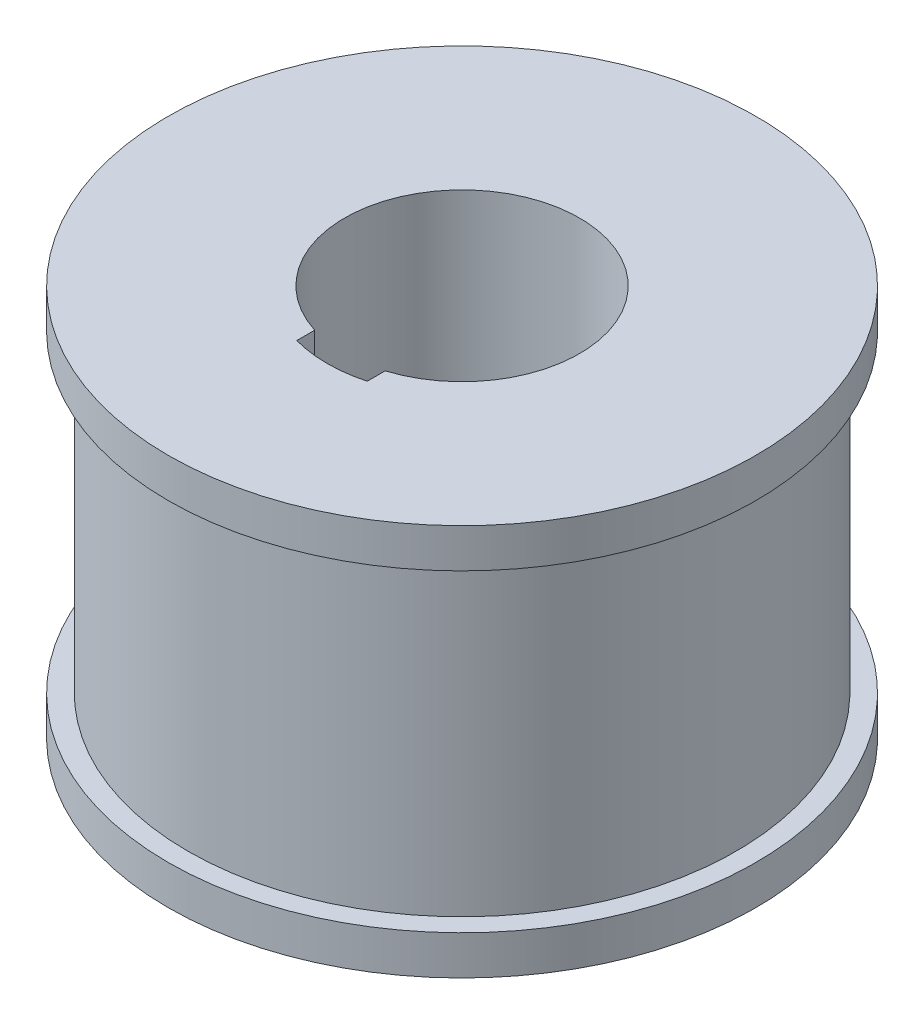
SolidWorks part; units mm, degrees
ref_plane "Front Plane" through (0, 0, 0) normal (0, 0, 1) x (1, 0, 0)
ref_plane "Top Plane" through (0, 0, 0) normal (0, 1, 0) x (1, 0, 0)
ref_plane "Right Plane" through (0, 0, 0) normal (1, 0, 0) x (0, 0, -1)
sketch "Sketch1" plane through (0, 0, 0) normal (0, 1, 0) x (1, 0, 0)
  circle A0 centre (0, 0) radius 70
  circle A1 centre (0, 0) radius 30
  dimension "D1" = 140
  dimension "D2" = 60
extrude "Boss-Extrude1" add sketch "Sketch1" along normal mid plane 80
sketch "Sketch2" plane through (0, 40, 0) normal (0, 1, 0) x (1, 0, 0)
  circle A1 centre (0, 0) radius 30 construction
  circle A2 centre (0, 0) radius 75
  circle A3 centre (0, 0) radius 75
  circle A4 centre (0, 0) radius 30
  dimension "D1" = 5
extrude "Boss-Extrude2" add sketch "Sketch2" along normal blind 10
mirror "Mirror1" about plane through (0, 0, 0) normal (0, 1, 0) of "Boss-Extrude2"
sketch "Sketch3" plane through (0, -50, 0) normal (0, -1, 0) x (1, 0, 0)
  line L0 (0, 19.4679) -> (0, 34.4) construction
  line L1 (-9, 33.2018) -> (-9, 19.4679)
  line L2 (9, 33.2018) -> (9, 19.4679)
  line L3 (-9, 19.4679) -> (9, 19.4679)
  circle A3 centre (0, 0) radius 34.4
  arc A4 (9, 33.2018) -> (-9, 33.2018) centre (0, 0) ccw
  dimension "D2" = 9
  dimension "D1" = 4.4
extrude "Cut-Extrude1" cut sketch "Sketch3" against normal through all
